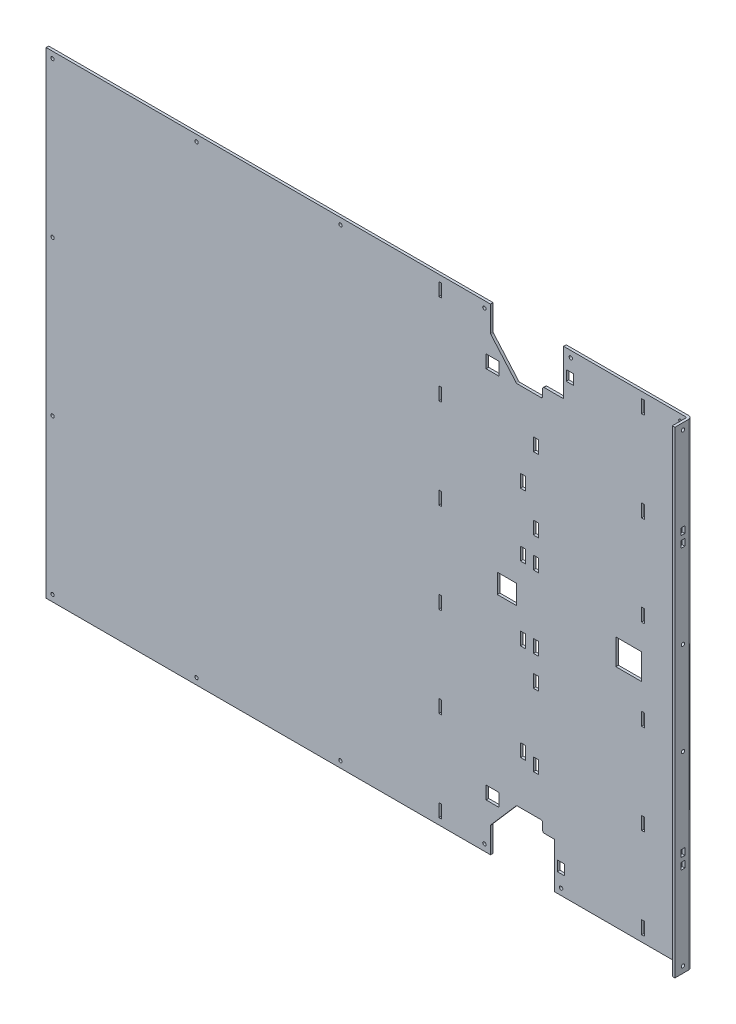
SolidWorks part; units mm, degrees
material "PC Высокая вязкость"
ref_plane "Спереди" through (0, 0, 0) normal (0, 0, 1) x (1, 0, 0)
ref_plane "Сверху" through (0, 0, 0) normal (0, 1, 0) x (1, 0, 0)
ref_plane "Справа" through (0, 0, 0) normal (1, 0, 0) x (0, 0, -1)
sketch "Эскиз1" plane through (0, 0, 0) normal (0, 0, 1) x (1, 0, 0)
  line L0 (994, 0) -> (0, 0)
  line L35 (994, 0) -> (994, 740)
  line L98 (0, 370) -> (50000, 370) construction
  line L2527 (0, 0) -> (0, 740)
  line L2528 (0, 740) -> (994, 740)
  point P31 (0, 370)
  dimension "D1" = 740
  dimension "D3" = 994
extrude "Бобышка-Вытянуть1" add sketch "Эскиз1" along normal blind 4
sketch "Эскиз9" plane through (0, 0, 0) normal (0, 0, -1) x (-1, 0, 0)
  line L0 (-788.5, 0) -> (-788.5, 70.1) construction
  line L1 (-788.5, 70.1) -> (-770, 70.1) construction
  line L2 (-770, 70.1) -> (-770, 86) construction
  line L3 (-690, 0) -> (-690, 40) construction
  line L4 (-690, 40) -> (-730, 86) construction
  line L5 (-802.5, 740) -> (-802.5, 669.9) construction
  line L6 (-730, 86) -> (-770, 86) construction
  line L7 (-994, 0) -> (-994, 740) construction
  line L8 (-690, 0) -> (-788.5, 0) construction
  line L9 (0, 740) -> (0, 0) construction
  line L10 (0, 0) -> (-994, 0) construction
  line L11 (-802.5, 669.9) -> (-770, 669.9) construction
  line L12 (-770, 669.9) -> (-770, 654) construction
  line L13 (-730, 654) -> (-770, 654) construction
  line L14 (-690, 740) -> (-802.5, 740) construction
  line L15 (-690, 700) -> (-730, 654) construction
  line L16 (0, 0) -> (-994, 0) construction
  line L17 (-690, 740) -> (-690, 700) construction
  line L18 (-994, 0) -> (-994, 740) construction
  line L19 (-994, 740) -> (0, 740) construction
  line L20 (-689.6, -0.4) -> (-788.9, -0.4)
  line L21 (-788.9, -0.4) -> (-788.9, 70.5)
  line L22 (-788.9, 70.5) -> (-770.4, 70.5)
  line L23 (-770.4, 70.5) -> (-770.4, 86.4)
  line L24 (-729.8177, 86.4) -> (-770.4, 86.4)
  line L25 (-689.6, 40.1496) -> (-729.8177, 86.4)
  line L26 (-689.6, -0.4) -> (-689.6, 40.1496)
  line L27 (-689.6, 740.4) -> (-802.9, 740.4)
  line L28 (-802.9, 740.4) -> (-802.9, 669.5)
  line L29 (-802.9, 669.5) -> (-770.4, 669.5)
  line L30 (-770.4, 669.5) -> (-770.4, 653.6)
  line L31 (-729.8177, 653.6) -> (-770.4, 653.6)
  line L32 (-689.6, 699.8504) -> (-729.8177, 653.6)
  line L33 (-689.6, 740.4) -> (-689.6, 699.8504)
  dimension "D1" = 40
  dimension "D2" = 86
  dimension "D3" = 15.9
  dimension "D4" = 70.1
  dimension "D5" = 40
  dimension "D6" = 86
  dimension "D7" = 40
  dimension "D8" = 0.4
  dimension "D9" = 0.4
  dimension "D10" = 32.5
  dimension "D11" = 70.1
  dimension "D12" = 40
  dimension "D13" = 15.9
  dimension "D14" = 40
  dimension "D15" = 18.5
  dimension "D16" = 770
extrude "Вырез-Вытянуть3" cut sketch "Эскиз9" against normal through all
sketch "Эскиз10" plane through (0, 0, 0) normal (0, 0, -1) x (-1, 0, 0)
  line L0 (-682.6378, 90.3459) -> (-709.7089, 63.2748) construction
  line L1 (-702.6378, 70.3459) -> (-682.6378, 70.3459)
  line L2 (-702.6378, 70.3459) -> (-702.6378, 90.3459)
  line L3 (-702.6378, 90.3459) -> (-682.6378, 90.3459)
  line L4 (-682.6378, 70.3459) -> (-682.6378, 90.3459)
  line L6 (-924, 350) -> (-884, 350)
  line L12 (-702.6378, 669.6541) -> (-682.6378, 669.6541)
  line L13 (-730, 355) -> (-700, 355)
  line L14 (-702.6378, 669.6541) -> (-702.6378, 649.6541)
  line L15 (-730, 385) -> (-730, 355)
  line L20 (-702.6378, 649.6541) -> (-682.6378, 649.6541)
  line L21 (-924, 390) -> (-924, 350)
  line L22 (-682.6378, 669.6541) -> (-682.6378, 649.6541)
  line L23 (-884, 390) -> (-924, 390)
  line L24 (-689.6, 40.1496) -> (-729.8177, 86.4) construction
  line L25 (-884, 350) -> (-884, 390)
  line L26 (-709.7089, 676.7252) -> (-682.6378, 649.6541) construction
  line L27 (-700, 385) -> (-730, 385)
  line L28 (-729.8177, 653.6) -> (-689.6, 699.8504) construction
  line L29 (-700, 355) -> (-700, 385)
  line L30 (0, 740) -> (0, 0) construction
  line L31 (0, 0) -> (-689.6, 0) construction
  line L32 (-994, 370) -> (49006, 370) construction
  line L33 (-994, 0) -> (-994, 740) construction
  point P20 (-709.7089, 63.2748)
  point P31 (-994, 370)
  point P32 (-730, 370)
  point P33 (-924, 370)
  dimension "D1" = 20
  dimension "D2" = 20
  dimension "D3" = 10
  dimension "D4" = 10
  dimension "D5" = 40
  dimension "D6" = 30
  dimension "D7" = 70
  dimension "D8" = 264
extrude "Вырез-Вытянуть4" cut sketch "Эскиз10" against normal through all
sketch "Эскиз11" plane through (0, 0, 0) normal (0, 0, -1) x (-1, 0, 0)
  line L1 (-994, 740) -> (-802.9, 740) construction
  line L3 (-788.9, 0) -> (-994, 0) construction
  line L4 (-804, 29.2) -> (-804, 45)
  line L5 (-804, 45) -> (-793, 45)
  line L6 (-793, 45) -> (-793, 29.2)
  line L7 (-793, 29.2) -> (-804, 29.2)
  line L8 (-770, 151.9472) -> (-770, 50151.9472) construction
  line L9 (0, 740) -> (0, 0) construction
  line L10 (-818, 695) -> (-818, 710.8)
  line L11 (-818, 710.8) -> (-807, 710.8)
  line L12 (-807, 710.8) -> (-807, 695)
  line L13 (-807, 695) -> (-818, 695)
  dimension "D1" = 15.8
  dimension "D2" = 11
  dimension "D3" = 29.2
  dimension "D4" = 770
  dimension "D5" = 23
  dimension "D6" = 15.8
  dimension "D7" = 11
  dimension "D8" = 29.2
  dimension "D9" = 37
extrude "Вырез-Вытянуть5" cut sketch "Эскиз11" against normal through all
sketch "Эскиз2" plane through (0, 0, 0) normal (0, 0, -1) x (-1, 0, 0)
  line L0 (0, 740) -> (0, 0) construction
  line L1 (0, 0) -> (-689.6, 0) construction
  line L2 (-10, 10) -> (-10, 250) construction
  line L3 (-10, 10) -> (-233.33, 10) construction
  line L4 (-689.6, 740) -> (0, 740) construction
  line L5 (-994, 0) -> (-994, 740) construction
  line L6 (-984, 10) -> (-799, 10) construction
  line L7 (-984, 10) -> (-984, 250) construction
  line L8 (-984, 730) -> (-814, 730) construction
  line L12 (-788.9, 0) -> (-994, 0) construction
  circle A0 centre (-10, 10) radius 2.6
  circle A1 centre (-10, 250) radius 2.6
  circle A2 centre (-10, 490) radius 2.6
  circle A3 centre (-10, 730) radius 2.6
  circle A16 centre (-984, 10) radius 2.6
  circle A17 centre (-984, 250) radius 2.6
  circle A18 centre (-984, 490) radius 2.6
  circle A19 centre (-984, 730) radius 2.6
  circle A24 centre (-233.33, 10) radius 2.6
  circle A25 centre (-233.33, 730) radius 2.6
  circle A26 centre (-456.66, 10) radius 2.6
  circle A27 centre (-456.66, 730) radius 2.6
  circle A28 centre (-679.99, 10) radius 2.6
  circle A29 centre (-679.99, 730) radius 2.6
  circle A30 centre (-799, 10) radius 2.6
  circle A32 centre (-799, 730) radius 2.6 [skipped]
  circle A33 centre (-814, 730) radius 2.6
  dimension "D1" = 5.2
  dimension "D10" = 5.2
  dimension "D15" = 185
  dimension "D17" = 170
  dimension "D2" = 10
  dimension "D3" = 10
  dimension "D5" = 240
  dimension "D7" = 223.33
  dimension "D9" = 2
  dimension "D11" = 10
  dimension "D12" = 10
  dimension "D14" = 240
  dimension "D16" = 2
  dimension "D8" = 10
  dimension "D4" = 4
  dimension "D13" = 4
  dimension "D6" = 4
extrude "Вырез-Вытянуть1" cut sketch "Эскиз2" against normal through all
sketch "Эскиз12" plane through (0, 0, 0) normal (0, 0, -1) x (-1, 0, 0)
  line L5 (0, 740) -> (0, 0) construction
  line L7 (-760, 86.4) -> (-760, 653.6) construction
  line L8 (-729.8177, 86.4) -> (-770.4, 86.4) construction
  line L9 (-770.4, 653.6) -> (-729.8177, 653.6) construction
  line L10 (-740, 653.6) -> (-740, 86.4) construction
  line L11 (0, 370) -> (-50000, 370) construction
  line L14 (-764, 304) -> (-756, 304)
  line L15 (-764, 304) -> (-764, 324)
  line L16 (-764, 324) -> (-756, 324)
  line L17 (-756, 304) -> (-756, 324)
  line L18 (-764, 304) -> (-756, 324) construction
  line L19 (-744, 304) -> (-736, 324) construction
  line L20 (-744, 304) -> (-736, 304)
  line L21 (-744, 304) -> (-744, 324)
  line L22 (-744, 324) -> (-736, 324)
  line L23 (-736, 304) -> (-736, 324)
  line L24 (-764, 257) -> (-756, 277) construction
  line L25 (-764, 257) -> (-756, 257)
  line L26 (-764, 257) -> (-764, 277)
  line L27 (-764, 277) -> (-756, 277)
  line L28 (-756, 257) -> (-756, 277)
  line L29 (-764, 145) -> (-756, 165) construction
  line L30 (-764, 145) -> (-756, 145)
  line L31 (-764, 145) -> (-764, 165)
  line L32 (-764, 165) -> (-756, 165)
  line L33 (-756, 145) -> (-756, 165)
  line L34 (-764, 416) -> (-756, 416)
  line L35 (-756, 436) -> (-756, 416)
  line L36 (-764, 436) -> (-756, 436)
  line L37 (-764, 436) -> (-764, 416)
  line L38 (-764, 463) -> (-756, 463)
  line L39 (-756, 483) -> (-756, 463)
  line L40 (-764, 483) -> (-756, 483)
  line L41 (-764, 483) -> (-764, 463)
  line L42 (-764, 575) -> (-756, 575)
  line L43 (-756, 595) -> (-756, 575)
  line L44 (-764, 595) -> (-756, 595)
  line L45 (-764, 595) -> (-764, 575)
  line L46 (-744, 154) -> (-736, 174) construction
  line L47 (-744, 154) -> (-736, 154)
  line L48 (-744, 154) -> (-744, 174)
  line L49 (-744, 174) -> (-736, 174)
  line L50 (-736, 154) -> (-736, 174)
  line L51 (-736, 535.85) -> (-744, 515.85) construction
  line L52 (-744, 418) -> (-736, 418)
  line L53 (-744, 418) -> (-744, 438)
  line L54 (-744, 438) -> (-736, 438)
  line L55 (-736, 418) -> (-736, 438)
  line L56 (-744, 515.85) -> (-736, 515.85)
  line L57 (-744, 515.85) -> (-744, 535.85)
  line L58 (-744, 535.85) -> (-736, 535.85)
  line L59 (-736, 515.85) -> (-736, 535.85)
  line L60 (-736, 438) -> (-744, 418) construction
  point P9 (0, 370)
  point P28 (-740, 164)
  point P40 (-760, 314)
  point P41 (-740, 314)
  point P43 (-760, 267)
  point P46 (-760, 155)
  point P62 (-740, 525.85)
  point P63 (-740, 428)
  dimension "D1" = 760
  dimension "D2" = 20
  dimension "D3" = 20
  dimension "D4" = 20
  dimension "D5" = 20
  dimension "D6" = 8
  dimension "D7" = 56
  dimension "D8" = 8
  dimension "D9" = 56
  dimension "D10" = 20
  dimension "D11" = 20
  dimension "D12" = 8
  dimension "D13" = 103
  dimension "D14" = 20
  dimension "D15" = 8
  dimension "D16" = 206
  dimension "D19" = 8
  dimension "D20" = 8
  dimension "D21" = 215
  dimension "D22" = 20
  dimension "D23" = 8
  dimension "D24" = 155.85
  dimension "D25" = 58
extrude "Вырез-Вытянуть6" cut sketch "Эскиз12" against normal through all
sketch "Эскиз13" plane through (0, 0, 0) normal (0, 0, -1) x (-1, 0, 0)
  line L1 (-994, 0) -> (-994, 740) construction
  line L27 (-613.6, 9.9) -> (-613.6, 30.1)
  line L48 (-613.6, 9.9) -> (-609.4, 9.9)
  line L49 (-788.9, 0) -> (-994, 0) construction
  line L50 (-928.1, 9.9) -> (-923.9, 9.9)
  line L51 (-928.1, 9.9) -> (-928.1, 30.1)
  line L52 (-928.1, 30.1) -> (-923.9, 30.1)
  line L53 (-923.9, 9.9) -> (-923.9, 30.1)
  line L74 (-928.1, 9.9) -> (-928.1, 149.9) construction
  line L77 (-609.4, 9.9) -> (-609.4, 30.1)
  line L78 (-613.6, 30.1) -> (-609.4, 30.1)
  line L79 (-613.6, 149.9) -> (-613.6, 170.1)
  line L80 (-613.6, 149.9) -> (-609.4, 149.9)
  line L81 (-609.4, 149.9) -> (-609.4, 170.1)
  line L82 (-613.6, 170.1) -> (-609.4, 170.1)
  line L83 (-613.6, 289.9) -> (-613.6, 310.1)
  line L84 (-613.6, 289.9) -> (-609.4, 289.9)
  line L85 (-609.4, 289.9) -> (-609.4, 310.1)
  line L86 (-613.6, 310.1) -> (-609.4, 310.1)
  line L87 (-613.6, 429.9) -> (-613.6, 450.1)
  line L88 (-613.6, 429.9) -> (-609.4, 429.9)
  line L89 (-609.4, 429.9) -> (-609.4, 450.1)
  line L90 (-613.6, 450.1) -> (-609.4, 450.1)
  line L91 (-613.6, 569.9) -> (-613.6, 590.1)
  line L92 (-613.6, 569.9) -> (-609.4, 569.9)
  line L93 (-609.4, 569.9) -> (-609.4, 590.1)
  line L94 (-613.6, 590.1) -> (-609.4, 590.1)
  line L95 (-613.6, 709.9) -> (-613.6, 730.1)
  line L96 (-613.6, 709.9) -> (-609.4, 709.9)
  line L97 (-609.4, 709.9) -> (-609.4, 730.1)
  line L98 (-613.6, 730.1) -> (-609.4, 730.1)
  line L99 (-928.1, 149.9) -> (-928.1, 170.1)
  line L100 (-928.1, 149.9) -> (-923.9, 149.9)
  line L101 (-923.9, 149.9) -> (-923.9, 170.1)
  line L102 (-928.1, 170.1) -> (-923.9, 170.1)
  line L103 (-928.1, 289.9) -> (-928.1, 310.1)
  line L104 (-928.1, 289.9) -> (-923.9, 289.9)
  line L105 (-923.9, 289.9) -> (-923.9, 310.1)
  line L106 (-928.1, 310.1) -> (-923.9, 310.1)
  line L107 (-928.1, 429.9) -> (-928.1, 450.1)
  line L108 (-928.1, 429.9) -> (-923.9, 429.9)
  line L109 (-923.9, 429.9) -> (-923.9, 450.1)
  line L110 (-928.1, 450.1) -> (-923.9, 450.1)
  line L111 (-928.1, 569.9) -> (-928.1, 590.1)
  line L112 (-928.1, 569.9) -> (-923.9, 569.9)
  line L113 (-923.9, 569.9) -> (-923.9, 590.1)
  line L114 (-928.1, 590.1) -> (-923.9, 590.1)
  line L115 (-928.1, 709.9) -> (-928.1, 730.1)
  line L116 (-928.1, 709.9) -> (-923.9, 709.9)
  line L117 (-923.9, 709.9) -> (-923.9, 730.1)
  line L118 (-928.1, 730.1) -> (-923.9, 730.1)
  line L119 (-928.1, 9.9) -> (-613.6, 9.9) construction
  line L120 (-928.1, 9.9) -> (-928.1, 149.9) construction
  point P66 (-928.1, 20)
  dimension "D5" = 314.5
  dimension "D6" = 140
  dimension "D2" = 2
  dimension "D4" = 90
  dimension "D3" = 6
  dimension "D12" = 20.2
  dimension "D13" = 4.2
  dimension "D14" = 20
  dimension "D15" = 70.1
  dimension "D17" = 140
extrude "Вырез-Вытянуть7" cut sketch "Эскиз13" against normal through all and the other way through all
sketch "Эскиз6" plane through (994, 0, 0) normal (1, 0, 0) x (0, 0, -1)
  line L0 (-4, 0) -> (-4, 740) construction
  line L1 (0, 740) -> (-26.45, 740)
  line L2 (0, 740) -> (0, 0)
  line L3 (0, 0) -> (-26.45, 0)
  line L4 (-26.45, 740) -> (-26.45, 0)
  line L9 (0, 0) -> (0, 740) construction
  dimension "D1" = 22.45
extrude "Бобышка-Вытянуть2" add sketch "Эскиз6" along normal blind 4
sketch "Эскиз8" plane through (998, 0, 0) normal (1, 0, 0) x (0, 0, -1)
  line L0 (-26.45, 370) -> (49973.55, 370) construction
  line L1 (-26.45, 740) -> (-26.45, 0) construction
  line L2 (-26.45, 0) -> (0, 0) construction
  line L3 (-16.88, 150.5) -> (-11.08, 150.5)
  line L4 (-16.88, 150.5) -> (-16.88, 140)
  line L5 (-16.88, 140) -> (-11.08, 140)
  line L6 (-11.08, 150.5) -> (-11.08, 140)
  line L7 (-16.88, 167.5) -> (-11.08, 167.5)
  line L8 (-16.88, 167.5) -> (-16.88, 157)
  line L9 (-16.88, 157) -> (-11.08, 157)
  line L10 (-11.08, 167.5) -> (-11.08, 157)
  line L11 (-16.88, 572.5) -> (-16.88, 583)
  line L12 (-16.88, 572.5) -> (-11.08, 572.5)
  line L13 (-11.08, 572.5) -> (-11.08, 583)
  line L14 (-16.88, 583) -> (-11.08, 583)
  line L15 (-16.88, 589.5) -> (-11.08, 589.5)
  line L16 (-16.88, 589.5) -> (-16.88, 600)
  line L17 (-16.88, 600) -> (-11.08, 600)
  line L18 (-11.08, 589.5) -> (-11.08, 600)
  point P4 (-26.45, 370)
  dimension "D1" = 10.5
  dimension "D2" = 6.5
  dimension "D3" = 10.5
  dimension "D4" = 5.8
  dimension "D5" = 9.57
  dimension "D6" = 140
extrude "Вырез-Вытянуть2" cut sketch "Эскиз8" against normal through all
sketch "Эскиз14" plane through (998, 0, 0) normal (1, 0, 0) x (0, 0, -1)
  line L1 (0, 0) -> (0, 740) construction
  line L2 (-26.45, 0) -> (0, 0) construction
  line L3 (-14, 10) -> (-14, 154) construction
  circle A0 centre (-14, 10) radius 2.6
  circle A2 centre (-14, 298) radius 2.6
  circle A3 centre (-14, 442) radius 2.6
  circle A5 centre (-14, 730) radius 2.6
  circle A6 centre (-14, 154) radius 2.6 [skipped]
  circle A7 centre (-14, 586) radius 2.6 [skipped]
  dimension "D1" = 5.2
  dimension "D2" = 14
  dimension "D3" = 10
  dimension "D5" = 144
  dimension "D4" = 6
extrude "Вырез-Вытянуть8" cut sketch "Эскиз14" against normal through all
fillet "Скругление1" radius 1.5 1 edges at (994, 370, 4)
fillet "Скругление2" radius 5.5 1 edges at (998, 370, 0)
fillet "Скругление4" radius 2.5 8 edges at (729.8177, 653.6, 2) (689.6, 699.8504, 2) (729.8177, 86.4, 2) (689.6, 40.1496, 2) (770.4, 669.5, 2) (770.4, 653.6, 2) (770.4, 70.5, 2) (770.4, 86.4, 2)
